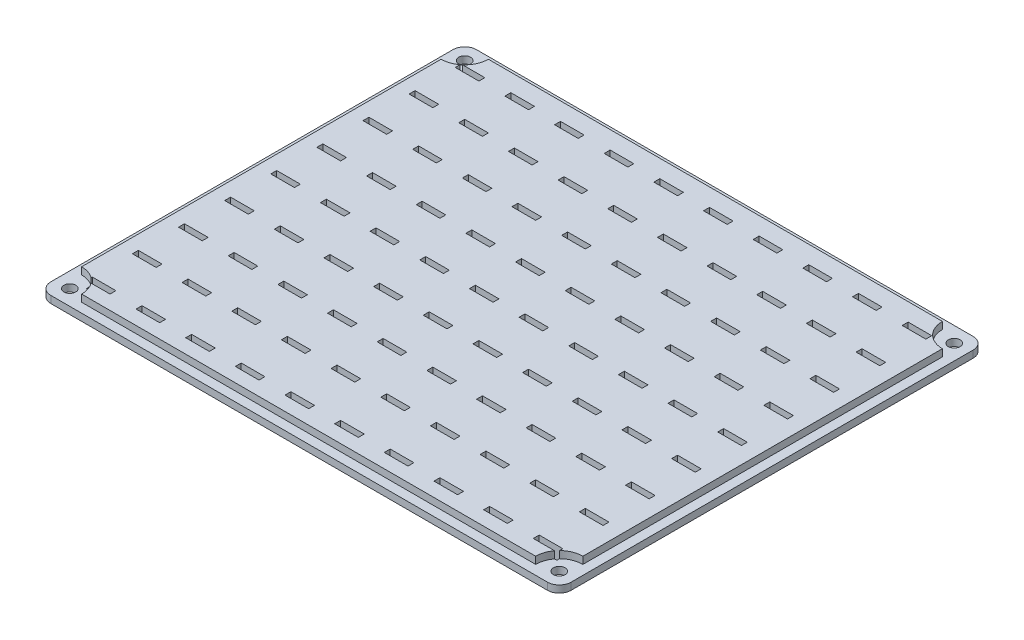
SolidWorks part; units mm, degrees
ref_plane "Front Plane" through (0, 0, 0) normal (0, 0, 1) x (1, 0, 0)
ref_plane "Top Plane" through (0, 0, 0) normal (0, 1, 0) x (1, 0, 0)
ref_plane "Right Plane" through (0, 0, 0) normal (1, 0, 0) x (0, 0, -1)
sketch "Sketch1" plane through (0, 0, 0) normal (0, 1, 0) x (1, 0, 0)
  line L1 (0, 0) -> (220, 0)
  line L2 (0, 0) -> (0, 180)
  line L3 (0, 180) -> (220, 180)
  line L4 (220, 0) -> (220, 180)
  dimension "D1" = 220
  dimension "D2" = 180
extrude "Boss-Extrude1" add sketch "Sketch1" along normal blind 3
fillet "Fillet1" radius 5 4 edges at (0, 1.5, -180) (0, 1.5, 0) (220, 1.5, -180) (220, 1.5, 0)
sketch "Sketch7" plane through (0, 3, 0) normal (0, 1, 0) x (1, 0, 0)
  line L0 (110, 187.4123) -> (110, -2.139) construction
  line L1 (-6.8646, 90) -> (231.1986, 90) construction
  line L2 (206, 176) -> (14, 176)
  line L3 (216, 166) -> (216, 14)
  line L4 (215, 180) -> (5, 180) construction
  line L5 (220, 5) -> (220, 175) construction
  line L6 (206, 4) -> (14, 4)
  line L7 (4, 166) -> (4, 14)
  line L8 (0, 175) -> (0, 5) construction
  line L9 (5, 0) -> (215, 0) construction
  arc A0 (206, 176) -> (216, 166) centre (216, 176) ccw
  arc A1 (206, 4) -> (216, 14) centre (216, 4) cw
  arc A2 (14, 4) -> (4, 14) centre (4, 4) ccw
  arc A3 (14, 176) -> (4, 166) centre (4, 176) cw
  point P14 (216, 90)
  point P18 (110, 4)
  point P23 (110, 176)
  dimension "D5" = 4
  dimension "D1" = 4
  dimension "D2" = 4
  dimension "D3" = 14
  dimension "D4" = 14
  dimension "D6" = 4
extrude "Boss-Extrude2" add sketch "Sketch7" along normal blind 3
sketch "Sketch8" plane through (0, 3, 0) normal (0, 1, 0) x (1, 0, 0)
  line L0 (110, 176) -> (110, 4) construction
  line L1 (206, 176) -> (14, 176) construction
  line L2 (14, 4) -> (206, 4) construction
  line L3 (4, 90) -> (216, 90) construction
  line L4 (4, 166) -> (4, 14) construction
  line L5 (216, 14) -> (216, 166) construction
  line L6 (215, 180) -> (5, 180) construction
  line L7 (0, 175) -> (0, 5) construction
  circle A0 centre (6.5, 173.5) radius 2.5
  circle A1 centre (213.5, 173.5) radius 2.5
  circle A2 centre (213.5, 6.5) radius 2.5
  circle A3 centre (6.5, 6.5) radius 2.5
  point P24 (0, 0)
  dimension "D1" = 5
  dimension "D2" = 6.5
  dimension "D3" = 6.5
extrude "Cut-Extrude3" cut sketch "Sketch8" against normal through all
sketch "Sketch9" plane through (0, 0, 0) normal (0, -1, 0) x (1, 0, 0)
  line L6 (31, -10) -> (31, -12.5)
  line L9 (31, -10) -> (41, -10)
  line L10 (10, -10) -> (20, -10)
  line L11 (10, -10) -> (10, -12.5)
  line L12 (10, -12.5) -> (20, -12.5)
  line L13 (20, -10) -> (20, -12.5)
  line L14 (41, -10) -> (41, -12.5)
  line L15 (31, -12.5) -> (41, -12.5)
  line L16 (52, -10) -> (52, -12.5)
  line L17 (52, -10) -> (62, -10)
  line L18 (62, -10) -> (62, -12.5)
  line L19 (52, -12.5) -> (62, -12.5)
  line L20 (73, -10) -> (73, -12.5)
  line L21 (73, -10) -> (83, -10)
  line L22 (83, -10) -> (83, -12.5)
  line L23 (73, -12.5) -> (83, -12.5)
  line L24 (94, -10) -> (94, -12.5)
  line L25 (94, -10) -> (104, -10)
  line L26 (104, -10) -> (104, -12.5)
  line L27 (94, -12.5) -> (104, -12.5)
  line L28 (115, -10) -> (115, -12.5)
  line L29 (115, -10) -> (125, -10)
  line L30 (125, -10) -> (125, -12.5)
  line L31 (115, -12.5) -> (125, -12.5)
  line L32 (136, -10) -> (136, -12.5)
  line L33 (136, -10) -> (146, -10)
  line L34 (146, -10) -> (146, -12.5)
  line L35 (136, -12.5) -> (146, -12.5)
  line L36 (157, -10) -> (157, -12.5)
  line L37 (157, -10) -> (167, -10)
  line L38 (167, -10) -> (167, -12.5)
  line L39 (157, -12.5) -> (167, -12.5)
  line L40 (178, -10) -> (178, -12.5)
  line L41 (178, -10) -> (188, -10)
  line L42 (188, -10) -> (188, -12.5)
  line L43 (178, -12.5) -> (188, -12.5)
  line L44 (199, -10) -> (199, -12.5)
  line L45 (199, -10) -> (209, -10)
  line L46 (209, -10) -> (209, -12.5)
  line L47 (199, -12.5) -> (209, -12.5)
  line L48 (31, -29.5) -> (31, -32)
  line L49 (31, -29.5) -> (41, -29.5)
  line L50 (41, -29.5) -> (41, -32)
  line L51 (31, -32) -> (41, -32)
  line L52 (52, -29.5) -> (52, -32)
  line L53 (52, -29.5) -> (62, -29.5)
  line L54 (62, -29.5) -> (62, -32)
  line L55 (52, -32) -> (62, -32)
  line L56 (73, -29.5) -> (73, -32)
  line L57 (73, -29.5) -> (83, -29.5)
  line L58 (83, -29.5) -> (83, -32)
  line L59 (73, -32) -> (83, -32)
  line L60 (94, -29.5) -> (94, -32)
  line L61 (94, -29.5) -> (104, -29.5)
  line L62 (104, -29.5) -> (104, -32)
  line L63 (94, -32) -> (104, -32)
  line L64 (115, -29.5) -> (115, -32)
  line L65 (115, -29.5) -> (125, -29.5)
  line L66 (125, -29.5) -> (125, -32)
  line L67 (115, -32) -> (125, -32)
  line L68 (136, -29.5) -> (136, -32)
  line L69 (136, -29.5) -> (146, -29.5)
  line L70 (146, -29.5) -> (146, -32)
  line L71 (136, -32) -> (146, -32)
  line L72 (157, -29.5) -> (157, -32)
  line L73 (157, -29.5) -> (167, -29.5)
  line L74 (167, -29.5) -> (167, -32)
  line L75 (157, -32) -> (167, -32)
  line L76 (178, -29.5) -> (178, -32)
  line L77 (178, -29.5) -> (188, -29.5)
  line L78 (188, -29.5) -> (188, -32)
  line L79 (178, -32) -> (188, -32)
  line L80 (199, -29.5) -> (199, -32)
  line L81 (199, -29.5) -> (209, -29.5)
  line L82 (209, -29.5) -> (209, -32)
  line L83 (199, -32) -> (209, -32)
  line L84 (31, -49) -> (31, -51.5)
  line L85 (31, -49) -> (41, -49)
  line L86 (41, -49) -> (41, -51.5)
  line L87 (31, -51.5) -> (41, -51.5)
  line L88 (52, -49) -> (52, -51.5)
  line L89 (52, -49) -> (62, -49)
  line L90 (62, -49) -> (62, -51.5)
  line L91 (52, -51.5) -> (62, -51.5)
  line L92 (73, -49) -> (73, -51.5)
  line L93 (73, -49) -> (83, -49)
  line L94 (83, -49) -> (83, -51.5)
  line L95 (73, -51.5) -> (83, -51.5)
  line L96 (94, -49) -> (94, -51.5)
  line L97 (94, -49) -> (104, -49)
  line L98 (104, -49) -> (104, -51.5)
  line L99 (94, -51.5) -> (104, -51.5)
  line L100 (115, -49) -> (115, -51.5)
  line L101 (115, -49) -> (125, -49)
  line L102 (125, -49) -> (125, -51.5)
  line L103 (115, -51.5) -> (125, -51.5)
  line L104 (136, -49) -> (136, -51.5)
  line L105 (136, -49) -> (146, -49)
  line L106 (146, -49) -> (146, -51.5)
  line L107 (136, -51.5) -> (146, -51.5)
  line L108 (157, -49) -> (157, -51.5)
  line L109 (157, -49) -> (167, -49)
  line L110 (167, -49) -> (167, -51.5)
  line L111 (157, -51.5) -> (167, -51.5)
  line L112 (178, -49) -> (178, -51.5)
  line L113 (178, -49) -> (188, -49)
  line L114 (188, -49) -> (188, -51.5)
  line L115 (178, -51.5) -> (188, -51.5)
  line L116 (199, -49) -> (199, -51.5)
  line L117 (199, -49) -> (209, -49)
  line L118 (209, -49) -> (209, -51.5)
  line L119 (199, -51.5) -> (209, -51.5)
  line L120 (31, -68.5) -> (31, -71)
  line L121 (31, -68.5) -> (41, -68.5)
  line L122 (41, -68.5) -> (41, -71)
  line L123 (31, -71) -> (41, -71)
  line L124 (52, -68.5) -> (52, -71)
  line L125 (52, -68.5) -> (62, -68.5)
  line L126 (62, -68.5) -> (62, -71)
  line L127 (52, -71) -> (62, -71)
  line L128 (73, -68.5) -> (73, -71)
  line L129 (73, -68.5) -> (83, -68.5)
  line L130 (83, -68.5) -> (83, -71)
  line L131 (73, -71) -> (83, -71)
  line L132 (94, -68.5) -> (94, -71)
  line L133 (94, -68.5) -> (104, -68.5)
  line L134 (104, -68.5) -> (104, -71)
  line L135 (94, -71) -> (104, -71)
  line L136 (115, -68.5) -> (115, -71)
  line L137 (115, -68.5) -> (125, -68.5)
  line L138 (125, -68.5) -> (125, -71)
  line L139 (115, -71) -> (125, -71)
  line L140 (136, -68.5) -> (136, -71)
  line L141 (136, -68.5) -> (146, -68.5)
  line L142 (146, -68.5) -> (146, -71)
  line L143 (136, -71) -> (146, -71)
  line L144 (157, -68.5) -> (157, -71)
  line L145 (157, -68.5) -> (167, -68.5)
  line L146 (167, -68.5) -> (167, -71)
  line L147 (157, -71) -> (167, -71)
  line L148 (178, -68.5) -> (178, -71)
  line L149 (178, -68.5) -> (188, -68.5)
  line L150 (188, -68.5) -> (188, -71)
  line L151 (178, -71) -> (188, -71)
  line L152 (199, -68.5) -> (199, -71)
  line L153 (199, -68.5) -> (209, -68.5)
  line L154 (209, -68.5) -> (209, -71)
  line L155 (199, -71) -> (209, -71)
  line L156 (31, -88) -> (31, -90.5)
  line L157 (31, -88) -> (41, -88)
  line L158 (41, -88) -> (41, -90.5)
  line L159 (31, -90.5) -> (41, -90.5)
  line L160 (52, -88) -> (52, -90.5)
  line L161 (52, -88) -> (62, -88)
  line L162 (62, -88) -> (62, -90.5)
  line L163 (52, -90.5) -> (62, -90.5)
  line L164 (73, -88) -> (73, -90.5)
  line L165 (73, -88) -> (83, -88)
  line L166 (83, -88) -> (83, -90.5)
  line L167 (73, -90.5) -> (83, -90.5)
  line L168 (94, -88) -> (94, -90.5)
  line L169 (94, -88) -> (104, -88)
  line L170 (104, -88) -> (104, -90.5)
  line L171 (94, -90.5) -> (104, -90.5)
  line L172 (115, -88) -> (115, -90.5)
  line L173 (115, -88) -> (125, -88)
  line L174 (125, -88) -> (125, -90.5)
  line L175 (115, -90.5) -> (125, -90.5)
  line L176 (136, -88) -> (136, -90.5)
  line L177 (136, -88) -> (146, -88)
  line L178 (146, -88) -> (146, -90.5)
  line L179 (136, -90.5) -> (146, -90.5)
  line L180 (157, -88) -> (157, -90.5)
  line L181 (157, -88) -> (167, -88)
  line L182 (167, -88) -> (167, -90.5)
  line L183 (157, -90.5) -> (167, -90.5)
  line L184 (178, -88) -> (178, -90.5)
  line L185 (178, -88) -> (188, -88)
  line L186 (188, -88) -> (188, -90.5)
  line L187 (178, -90.5) -> (188, -90.5)
  line L188 (199, -88) -> (199, -90.5)
  line L189 (199, -88) -> (209, -88)
  line L190 (209, -88) -> (209, -90.5)
  line L191 (199, -90.5) -> (209, -90.5)
  line L192 (31, -107.5) -> (31, -110)
  line L193 (31, -107.5) -> (41, -107.5)
  line L194 (41, -107.5) -> (41, -110)
  line L195 (31, -110) -> (41, -110)
  line L196 (52, -107.5) -> (52, -110)
  line L197 (52, -107.5) -> (62, -107.5)
  line L198 (62, -107.5) -> (62, -110)
  line L199 (52, -110) -> (62, -110)
  line L200 (73, -107.5) -> (73, -110)
  line L201 (73, -107.5) -> (83, -107.5)
  line L202 (83, -107.5) -> (83, -110)
  line L203 (73, -110) -> (83, -110)
  line L204 (94, -107.5) -> (94, -110)
  line L205 (94, -107.5) -> (104, -107.5)
  line L206 (104, -107.5) -> (104, -110)
  line L207 (94, -110) -> (104, -110)
  line L208 (115, -107.5) -> (115, -110)
  line L209 (115, -107.5) -> (125, -107.5)
  line L210 (125, -107.5) -> (125, -110)
  line L211 (115, -110) -> (125, -110)
  line L212 (136, -107.5) -> (136, -110)
  line L213 (136, -107.5) -> (146, -107.5)
  line L214 (146, -107.5) -> (146, -110)
  line L215 (136, -110) -> (146, -110)
  line L216 (157, -107.5) -> (157, -110)
  line L217 (157, -107.5) -> (167, -107.5)
  line L218 (167, -107.5) -> (167, -110)
  line L219 (157, -110) -> (167, -110)
  line L220 (178, -107.5) -> (178, -110)
  line L221 (178, -107.5) -> (188, -107.5)
  line L222 (188, -107.5) -> (188, -110)
  line L223 (178, -110) -> (188, -110)
  line L224 (199, -107.5) -> (199, -110)
  line L225 (199, -107.5) -> (209, -107.5)
  line L226 (209, -107.5) -> (209, -110)
  line L227 (199, -110) -> (209, -110)
  line L228 (31, -127) -> (31, -129.5)
  line L229 (31, -127) -> (41, -127)
  line L230 (41, -127) -> (41, -129.5)
  line L231 (31, -129.5) -> (41, -129.5)
  line L232 (52, -127) -> (52, -129.5)
  line L233 (52, -127) -> (62, -127)
  line L234 (62, -127) -> (62, -129.5)
  line L235 (52, -129.5) -> (62, -129.5)
  line L236 (73, -127) -> (73, -129.5)
  line L237 (73, -127) -> (83, -127)
  line L238 (83, -127) -> (83, -129.5)
  line L239 (73, -129.5) -> (83, -129.5)
  line L240 (94, -127) -> (94, -129.5)
  line L241 (94, -127) -> (104, -127)
  line L242 (104, -127) -> (104, -129.5)
  line L243 (94, -129.5) -> (104, -129.5)
  line L244 (115, -127) -> (115, -129.5)
  line L245 (115, -127) -> (125, -127)
  line L246 (125, -127) -> (125, -129.5)
  line L247 (115, -129.5) -> (125, -129.5)
  line L248 (136, -127) -> (136, -129.5)
  line L249 (136, -127) -> (146, -127)
  line L250 (146, -127) -> (146, -129.5)
  line L251 (136, -129.5) -> (146, -129.5)
  line L252 (157, -127) -> (157, -129.5)
  line L253 (157, -127) -> (167, -127)
  line L254 (167, -127) -> (167, -129.5)
  line L255 (157, -129.5) -> (167, -129.5)
  line L256 (178, -127) -> (178, -129.5)
  line L257 (178, -127) -> (188, -127)
  line L258 (188, -127) -> (188, -129.5)
  line L259 (178, -129.5) -> (188, -129.5)
  line L260 (199, -127) -> (199, -129.5)
  line L261 (199, -127) -> (209, -127)
  line L262 (209, -127) -> (209, -129.5)
  line L263 (199, -129.5) -> (209, -129.5)
  line L264 (31, -146.5) -> (31, -149)
  line L265 (31, -146.5) -> (41, -146.5)
  line L266 (41, -146.5) -> (41, -149)
  line L267 (31, -149) -> (41, -149)
  line L268 (52, -146.5) -> (52, -149)
  line L269 (52, -146.5) -> (62, -146.5)
  line L270 (62, -146.5) -> (62, -149)
  line L271 (52, -149) -> (62, -149)
  line L272 (73, -146.5) -> (73, -149)
  line L273 (73, -146.5) -> (83, -146.5)
  line L274 (83, -146.5) -> (83, -149)
  line L275 (73, -149) -> (83, -149)
  line L276 (94, -146.5) -> (94, -149)
  line L277 (94, -146.5) -> (104, -146.5)
  line L278 (104, -146.5) -> (104, -149)
  line L279 (94, -149) -> (104, -149)
  line L280 (115, -146.5) -> (115, -149)
  line L281 (115, -146.5) -> (125, -146.5)
  line L282 (125, -146.5) -> (125, -149)
  line L283 (115, -149) -> (125, -149)
  line L284 (136, -146.5) -> (136, -149)
  line L285 (136, -146.5) -> (146, -146.5)
  line L286 (146, -146.5) -> (146, -149)
  line L287 (136, -149) -> (146, -149)
  line L288 (157, -146.5) -> (157, -149)
  line L289 (157, -146.5) -> (167, -146.5)
  line L290 (167, -146.5) -> (167, -149)
  line L291 (157, -149) -> (167, -149)
  line L292 (178, -146.5) -> (178, -149)
  line L293 (178, -146.5) -> (188, -146.5)
  line L294 (188, -146.5) -> (188, -149)
  line L295 (178, -149) -> (188, -149)
  line L296 (199, -146.5) -> (199, -149)
  line L297 (199, -146.5) -> (209, -146.5)
  line L298 (209, -146.5) -> (209, -149)
  line L299 (199, -149) -> (209, -149)
  line L300 (31, -166) -> (31, -168.5)
  line L301 (31, -166) -> (41, -166)
  line L302 (41, -166) -> (41, -168.5)
  line L303 (31, -168.5) -> (41, -168.5)
  line L304 (52, -166) -> (52, -168.5)
  line L305 (52, -166) -> (62, -166)
  line L306 (62, -166) -> (62, -168.5)
  line L307 (52, -168.5) -> (62, -168.5)
  line L308 (73, -166) -> (73, -168.5)
  line L309 (73, -166) -> (83, -166)
  line L310 (83, -166) -> (83, -168.5)
  line L311 (73, -168.5) -> (83, -168.5)
  line L312 (94, -166) -> (94, -168.5)
  line L313 (94, -166) -> (104, -166)
  line L314 (104, -166) -> (104, -168.5)
  line L315 (94, -168.5) -> (104, -168.5)
  line L316 (115, -166) -> (115, -168.5)
  line L317 (115, -166) -> (125, -166)
  line L318 (125, -166) -> (125, -168.5)
  line L319 (115, -168.5) -> (125, -168.5)
  line L320 (136, -166) -> (136, -168.5)
  line L321 (136, -166) -> (146, -166)
  line L322 (146, -166) -> (146, -168.5)
  line L323 (136, -168.5) -> (146, -168.5)
  line L324 (157, -166) -> (157, -168.5)
  line L325 (157, -166) -> (167, -166)
  line L326 (167, -166) -> (167, -168.5)
  line L327 (157, -168.5) -> (167, -168.5)
  line L328 (178, -166) -> (178, -168.5)
  line L329 (178, -166) -> (188, -166)
  line L330 (188, -166) -> (188, -168.5)
  line L331 (178, -168.5) -> (188, -168.5)
  line L332 (199, -166) -> (199, -168.5)
  line L333 (199, -166) -> (209, -166)
  line L334 (209, -166) -> (209, -168.5)
  line L335 (199, -168.5) -> (209, -168.5)
  line L336 (10, -29.5) -> (10, -32)
  line L337 (10, -29.5) -> (20, -29.5)
  line L338 (20, -29.5) -> (20, -32)
  line L339 (10, -32) -> (20, -32)
  line L340 (10, -49) -> (10, -51.5)
  line L341 (10, -49) -> (20, -49)
  line L342 (20, -49) -> (20, -51.5)
  line L343 (10, -51.5) -> (20, -51.5)
  line L344 (10, -68.5) -> (10, -71)
  line L345 (10, -68.5) -> (20, -68.5)
  line L346 (20, -68.5) -> (20, -71)
  line L347 (10, -71) -> (20, -71)
  line L348 (10, -88) -> (10, -90.5)
  line L349 (10, -88) -> (20, -88)
  line L350 (20, -88) -> (20, -90.5)
  line L351 (10, -90.5) -> (20, -90.5)
  line L352 (10, -107.5) -> (10, -110)
  line L353 (10, -107.5) -> (20, -107.5)
  line L354 (20, -107.5) -> (20, -110)
  line L355 (10, -110) -> (20, -110)
  line L356 (10, -127) -> (10, -129.5)
  line L357 (10, -127) -> (20, -127)
  line L358 (20, -127) -> (20, -129.5)
  line L359 (10, -129.5) -> (20, -129.5)
  line L360 (10, -146.5) -> (10, -149)
  line L361 (10, -146.5) -> (20, -146.5)
  line L362 (20, -146.5) -> (20, -149)
  line L363 (10, -149) -> (20, -149)
  line L364 (10, -166) -> (10, -168.5)
  line L365 (10, -166) -> (20, -166)
  line L366 (20, -166) -> (20, -168.5)
  line L367 (10, -168.5) -> (20, -168.5)
  dimension "D5" = 10
  dimension "D6" = 2.5
  dimension "D8" = 10
  dimension "D9" = 10
  dimension "D10" = 9
extrude "Cut-Extrude4" cut sketch "Sketch9" against normal through all
